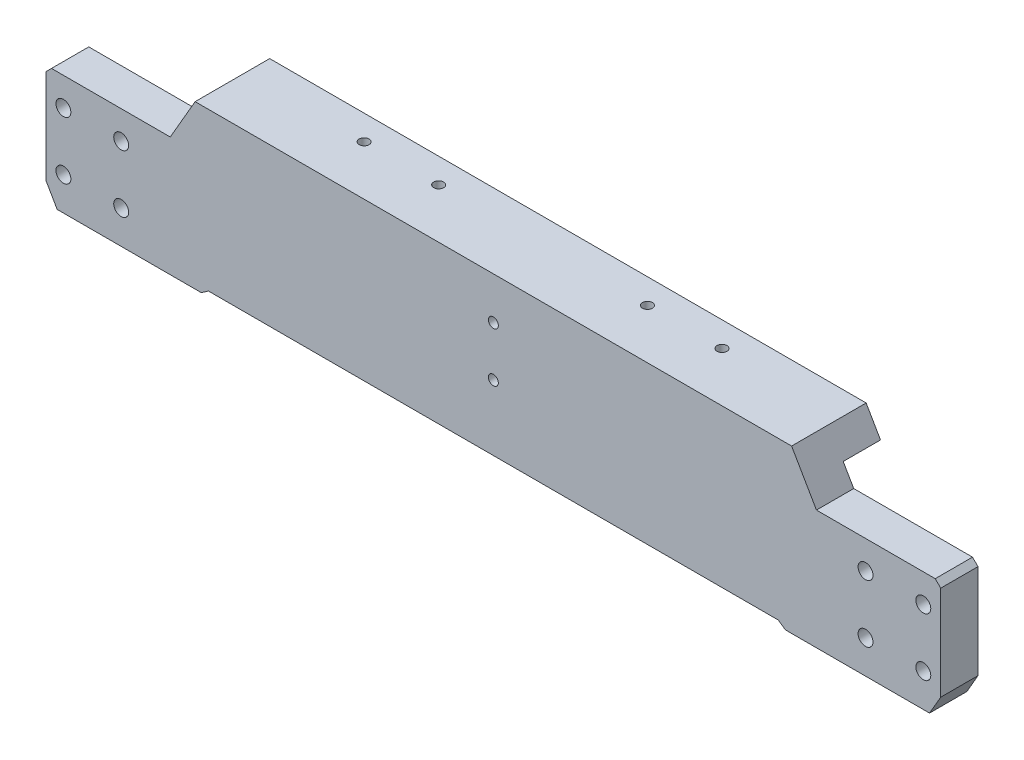
SolidWorks part; units mm, degrees
material "Balsa"
ref_plane "Front Plane" through (0, 0, 0) normal (0, 0, 1) x (1, 0, 0)
ref_plane "Top Plane" through (0, 0, 0) normal (0, 1, 0) x (1, 0, 0)
ref_plane "Right Plane" through (0, 0, 0) normal (1, 0, 0) x (0, 0, -1)
sketch "Sketch1" plane through (0, 0, 0) normal (0, 0, 1) x (1, 0, 0)
  line L0 (-114.6277, 0) -> (114.6277, 0)
  line L1 (114.6277, 0) -> (117.5, -2)
  line L2 (117.5, -2) -> (175.5, -2)
  line L3 (175.5, -2) -> (180, 5.7942)
  line L4 (180, 5.7942) -> (180, 43.7942)
  line L5 (180, 43.7942) -> (177.7942, 46)
  line L6 (177.7942, 46) -> (130, 46)
  line L7 (130, 46) -> (120, 63.3205)
  line L8 (120, 63.3205) -> (-120, 63.3205)
  line L9 (-120, 63.3205) -> (-130, 46)
  line L10 (-130, 46) -> (-177.7942, 46)
  line L11 (-177.7942, 46) -> (-180, 43.7942)
  line L12 (-180, 43.7942) -> (-180, 5.7942)
  line L13 (-180, 5.7942) -> (-175.5, -2)
  line L14 (-175.5, -2) -> (-117.5, -2)
  line L15 (-117.5, -2) -> (-114.6277, 0)
  line L16 (221.3361, 23) -> (-244.0467, 23) construction
  line L17 (0, 109.2548) -> (0, -63.3669) construction
  circle A0 centre (-173, 34.625) radius 3
  circle A1 centre (-149.75, 34.625) radius 3
  circle A2 centre (-173, 11.375) radius 3
  circle A3 centre (-149.75, 11.375) radius 3
  circle A10 centre (149.75, 34.625) radius 3
  circle A11 centre (173, 34.625) radius 3
  circle A12 centre (149.75, 11.375) radius 3
  circle A13 centre (173, 11.375) radius 3
  circle A14 centre (0, 46.3205) radius 2
  circle A15 centre (0, 26.3205) radius 2
  point P24 (0, 0)
  dimension "D1" = 360
  dimension "D2" = 6
  dimension "D3" = 23.25
  dimension "D4" = 46
  dimension "D5" = 48
  dimension "D6" = 7
  dimension "D7" = 23
  dimension "D8" = 23.25
  dimension "D9" = 11.625
  dimension "D11" = 7
  dimension "D13" = 20
  dimension "D14" = 17
  dimension "D15" = 4
  dimension "D16" = 240
  dimension "D10" = 11.625
  dimension "D12" = 180
  dimension "D17" = 120
  dimension "D18" = 120
  dimension "D19" = 58
  dimension "D20" = 3.5
  dimension "D21" = 120
  dimension "D22" = 50
  dimension "D23" = 135
  dimension "D24" = 135
  dimension "D25" = 120
  dimension "D26" = 120
  dimension "D27" = 38
  dimension "D28" = 9
extrude "Boss-Extrude1" add sketch "Sketch1" along normal blind 15
sketch "Sketch3" plane through (0, 0, 0) normal (0, 0, -1) x (-1, 0, 0)
  line L0 (-120, 63.3205) -> (120, 63.3205)
  line L1 (120, 63.3205) -> (125.7735, 53.3205)
  line L2 (120, 63.3205) -> (130, 46) construction
  line L3 (125.7735, 53.3205) -> (-125.7735, 53.3205)
  line L4 (-130, 46) -> (-120, 63.3205) construction
  line L5 (-125.7735, 53.3205) -> (-120, 63.3205)
  line L7 (-10.3723, 53.3205) -> (59.6277, 53.3205)
  line L8 (-10.3723, 53.3205) -> (-10.3723, 13.3205)
  line L9 (-10.3723, 13.3205) -> (59.6277, 13.3205)
  line L10 (59.6277, 53.3205) -> (59.6277, 13.3205)
  line M13 (130, 46) -> (120, 63.3205)
  line M14 (120, 63.3205) -> (-120, 63.3205)
  line M15 (-120, 63.3205) -> (-130, 46)
  circle M31 centre (0, 46.3205) radius 2
  circle M32 centre (0, 26.3205) radius 2
  dimension "D1" = 10
  dimension "D2" = 40
  dimension "D3" = 55
  dimension "D4" = 70
extrude "Boss-Extrude2" add sketch "Sketch3" along normal blind 15 contours L10 L3 L8 L9 M32 M31 | L3 M13 M14 M15
sketch "Sketch4" plane through (0, 63.3205, 0) normal (0, 1, 0) x (1, 0, 0)
  line L0 (0, 63.0714) -> (0, -67.5971) construction
  line L2 (120, -15) -> (120, 15) construction
  line L4 (-120, 15) -> (120, 15) construction
  circle A0 centre (-72, 5) radius 2
  circle A1 centre (-42, 5) radius 2
  circle A2 centre (42, 5) radius 2
  circle A3 centre (72, 5) radius 2
  dimension "D1" = 72
  dimension "D2" = 30
  dimension "D4" = 10
  dimension "D5" = 4
  dimension "D3" = 120
extrude "Cut-Extrude1" cut sketch "Sketch4" against normal through all
sketch "Esquisse1" plane through (0, 0, -15) normal (0, 0, -1) x (-1, 0, 0)
  line L0 (120, 63.3205) -> (-120, 63.3205) construction
  line L1 (-10.3723, 53.3205) -> (-10.3723, 13.3205) construction
  circle A0 centre (-50.3723, 58.3205) radius 2
  circle A1 centre (-63.3723, 58.3205) radius 2
  dimension "D1" = 4
  dimension "D2" = 5
  dimension "D3" = 40
  dimension "D4" = 13
extrude "Enlèv. mat.-Extru.1" cut sketch "Esquisse1" against normal blind 10
